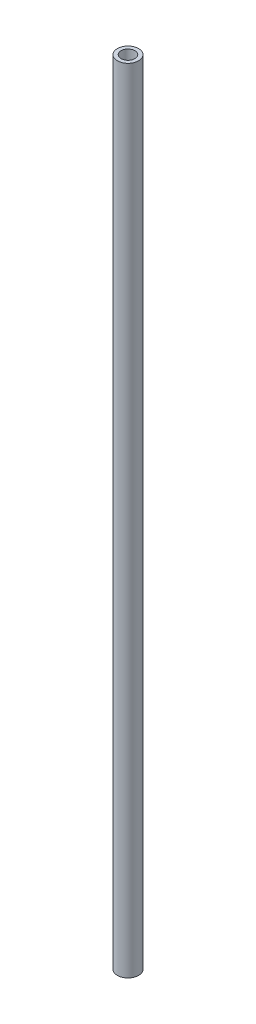
SolidWorks part; units mm, degrees
material "Silicon"
ref_plane "Front Plane" through (0, 0, 0) normal (0, 0, 1) x (1, 0, 0)
ref_plane "Top Plane" through (0, 0, 0) normal (0, 1, 0) x (1, 0, 0)
ref_plane "Right Plane" through (0, 0, 0) normal (1, 0, 0) x (0, 0, -1)
sketch "Sketch1" plane through (0, 0, 0) normal (0, 1, 0) x (1, 0, 0)
  circle A0 centre (0, 0) radius 3.35
  dimension "D1" = 6.7
extrude "Boss-Extrude1" add sketch "Sketch1" along normal blind 250
sketch "Sketch2" plane through (0, 250, 0) normal (0, 1, 0) x (1, 0, 0)
  circle A0 centre (0, 0) radius 2.184
extrude "Cut-Extrude1" cut sketch "Sketch2" against normal through all
